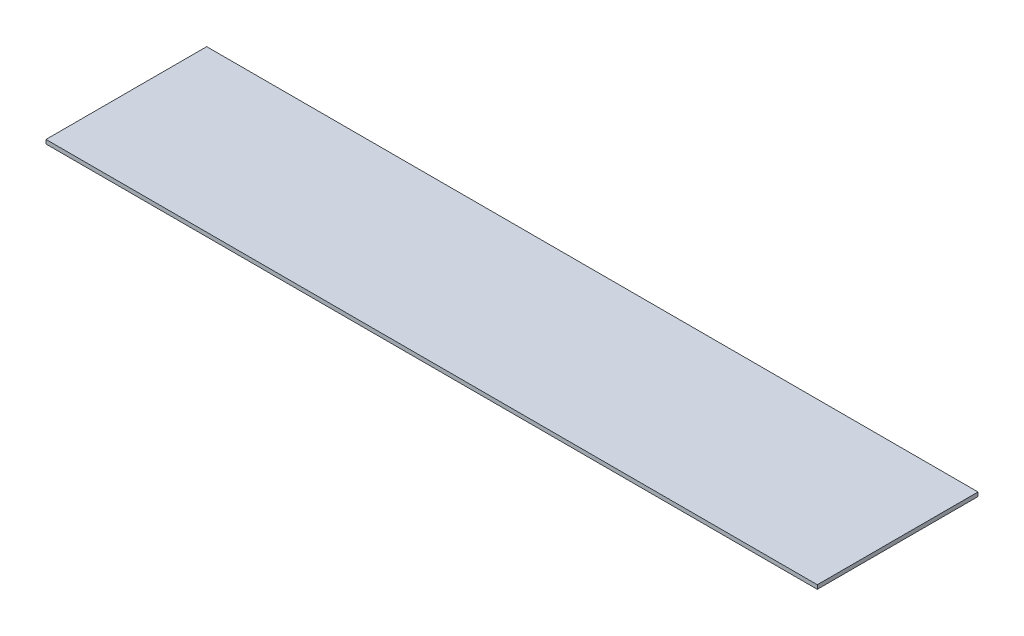
SolidWorks part; units mm, degrees
ref_plane "Front Plane" through (0, 0, 0) normal (0, 0, 1) x (1, 0, 0)
ref_plane "Top Plane" through (0, 0, 0) normal (0, 1, 0) x (1, 0, 0)
ref_plane "Right Plane" through (0, 0, 0) normal (1, 0, 0) x (0, 0, -1)
sketch "Sketch1" plane through (0, 0, 0) normal (0, 1, 0) x (1, 0, 0)
  line L1 (0, 0) -> (1219.2, 0)
  line L2 (0, 0) -> (0, 254)
  line L3 (0, 254) -> (1219.2, 254)
  line L4 (1219.2, 0) -> (1219.2, 254)
  dimension "D1" = 254
  dimension "D2" = 1219.2
extrude "Extrude1" add sketch "Sketch1" along normal blind 6.35
